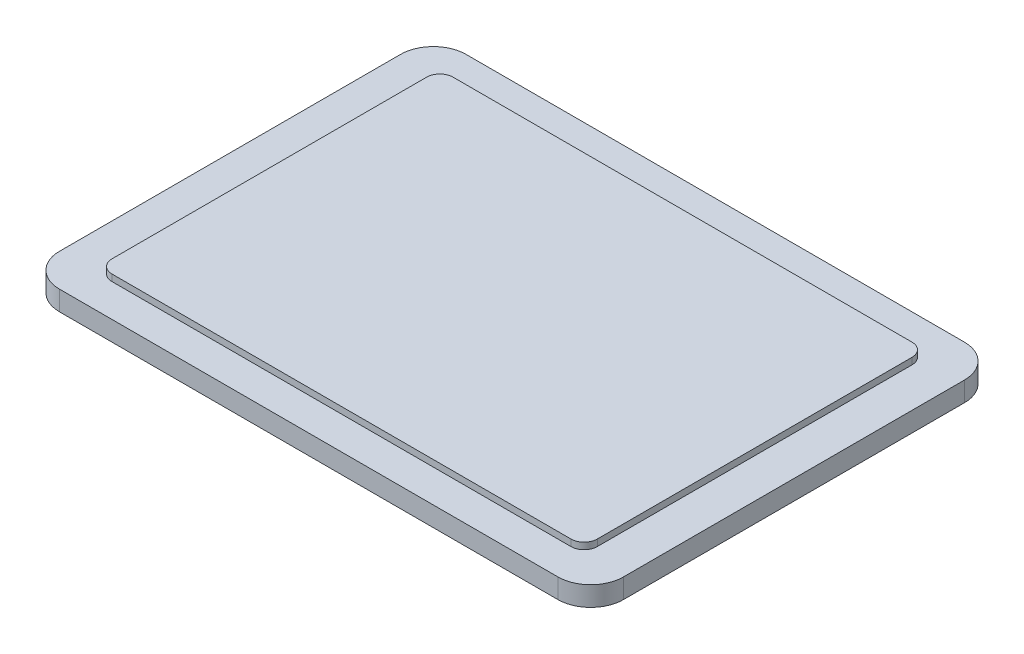
SolidWorks part; units mm, degrees
ref_plane "前视基准面" through (0, 0, 0) normal (0, 0, 1) x (1, 0, 0)
ref_plane "上视基准面" through (0, 0, 0) normal (0, 1, 0) x (1, 0, 0)
ref_plane "右视基准面" through (0, 0, 0) normal (1, 0, 0) x (0, 0, -1)
other "Configuration Table"
sketch "草图1" plane through (0, 0, 0) normal (0, 1, 0) x (1, 0, 0)
  line L1 (43, -31) -> (-43, -31)
  line L2 (43, -31) -> (43, 31)
  line L3 (43, 31) -> (-43, 31)
  line L4 (-43, -31) -> (-43, 31)
  line L5 (43, -31) -> (-43, 31) construction
  line L6 (43, 31) -> (-43, -31) construction
  point P0 (0, 0)
  dimension "D1" = 86
  dimension "D2" = 62
extrude "凸台-拉伸1" add sketch "草图1" along normal blind 3
sketch "草图2" plane through (0, 3, 0) normal (0, 1, 0) x (1, 0, 0)
  line L1 (37, -26) -> (-37, -26)
  line L2 (37, -26) -> (37, 26)
  line L3 (37, 26) -> (-37, 26)
  line L4 (-37, -26) -> (-37, 26)
  line L5 (37, -26) -> (-37, 26) construction
  line L6 (37, 26) -> (-37, -26) construction
  point P0 (0, 0)
  dimension "D1" = 74
  dimension "D2" = 52
extrude "凸台-拉伸2" add sketch "草图2" along normal blind 1
fillet "圆角1" radius 5 4 edges at (-43, 1.5, -31) (43, 1.5, -31) (43, 1.5, 31) (-43, 1.5, 31)
fillet "圆角2" radius 2 4 edges at (37, 3.5, 26) (-37, 3.5, 26) (37, 3.5, -26) (-37, 3.5, -26)
